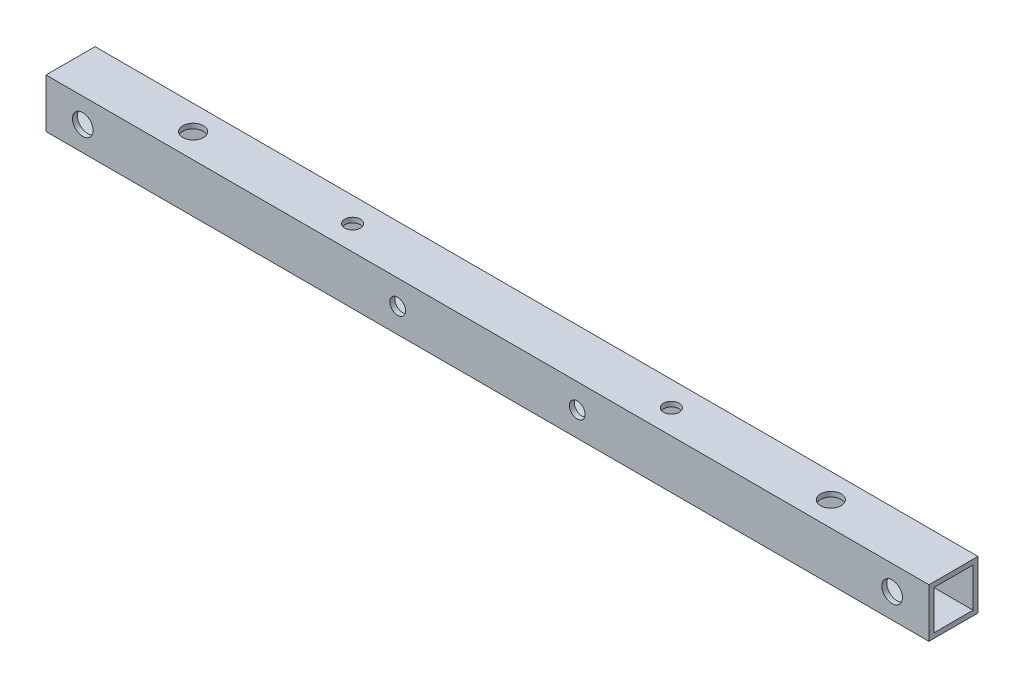
SolidWorks part; units mm, degrees
material "5052-H34"
ref_plane "正面" through (0, 0, 0) normal (0, 0, 1) x (1, 0, 0)
ref_plane "平面" through (0, 0, 0) normal (0, 1, 0) x (1, 0, 0)
ref_plane "右側面" through (0, 0, 0) normal (1, 0, 0) x (0, 0, -1)
sketch "ｽｹｯﾁ1" plane through (0, 0, 0) normal (1, 0, 0) x (0, 0, -1)
  line L1 (-5, 5) -> (5, 5)
  line L2 (-5, 5) -> (-5, -5)
  line L3 (-5, -5) -> (5, -5)
  line L4 (5, 5) -> (5, -5)
  line L5 (-5, 5) -> (5, -5) construction
  line L6 (-5, -5) -> (5, 5) construction
  point P0 (0, 0)
  dimension "D1" = 10
extrude "押し出し-薄板1" add sketch "ｽｹｯﾁ1" along normal blind 180 thin
sketch "ｽｹｯﾁ2" plane through (0, 0, 5) normal (0, 0, 1) x (1, 0, 0)
  line L0 (90, 5) -> (90, -5) construction
  line L1 (180, 5) -> (0, 5) construction
  line L2 (180, -5) -> (0, -5) construction
  line L3 (0, 0) -> (7.5, 0) construction
  circle A0 centre (7.5, 0) radius 2.1
  circle A1 centre (172.5, 0) radius 2.1
  dimension "D1" = 4.2
  dimension "D2" = 7.5
extrude "ｶｯﾄ - 押し出し1" cut sketch "ｽｹｯﾁ2" against normal through all
sketch "ｽｹｯﾁ3" plane through (0, 5, 0) normal (0, 1, 0) x (1, 0, 0)
  line L0 (90, 5) -> (90, -5) construction
  line L1 (180, 5) -> (0, 5) construction
  line L2 (180, -5) -> (0, -5) construction
  line L3 (0, 0) -> (25, 0) construction
  circle A0 centre (25, 0) radius 2.1
  circle A1 centre (155, 0) radius 2.1
  dimension "D1" = 4.2
  dimension "D2" = 25
extrude "ｶｯﾄ - 押し出し2" cut sketch "ｽｹｯﾁ3" against normal through all
sketch "ｽｹｯﾁ4" plane through (0, 0, 5) normal (0, 0, 1) x (1, 0, 0)
  line L0 (90, 5) -> (90, -5) construction
  line L1 (180, 5) -> (0, 5) construction
  line L2 (180, -5) -> (0, -5) construction
  line L3 (90, 0) -> (71.7, 0) construction
  circle A0 centre (71.7, 0) radius 1.6
  circle A1 centre (108.3, 0) radius 1.6
  dimension "D1" = 3.2
  dimension "D2" = 36.6
extrude "ｶｯﾄ - 押し出し3" cut sketch "ｽｹｯﾁ4" against normal through all
sketch "ｽｹｯﾁ5" plane through (0, 5, 0) normal (0, 1, 0) x (1, 0, 0)
  line L0 (90, 5) -> (90, -5) construction
  line L1 (180, 5) -> (0, 5) construction
  line L2 (180, -5) -> (0, -5) construction
  line L3 (90, 0) -> (57.5, 0) construction
  circle A0 centre (57.5, 0) radius 1.6
  circle A1 centre (122.5, 0) radius 1.6
  dimension "D1" = 3.2
  dimension "D2" = 65
extrude "ｶｯﾄ - 押し出し4" cut sketch "ｽｹｯﾁ5" against normal through all
